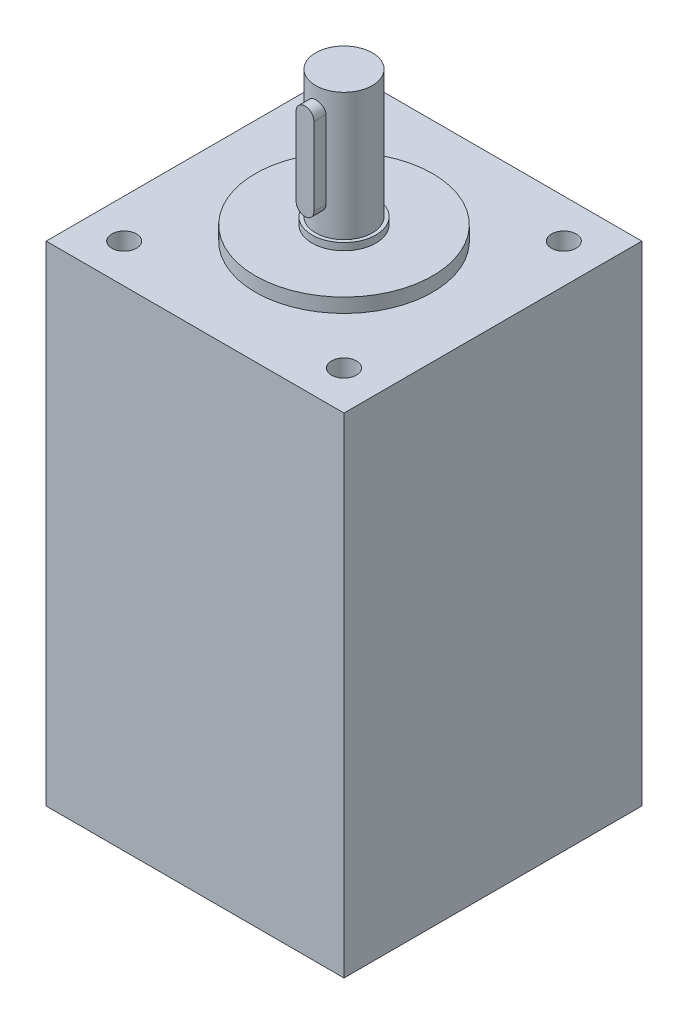
SolidWorks part; units mm, degrees
ref_plane "前视基准面" through (0, 0, 0) normal (0, 0, 1) x (1, 0, 0)
ref_plane "上视基准面" through (0, 0, 0) normal (0, 1, 0) x (1, 0, 0)
ref_plane "右视基准面" through (0, 0, 0) normal (1, 0, 0) x (0, 0, -1)
other "Configuration Table"
sketch "草图2" plane through (0, 0, 0) normal (0, 1, 0) x (1, 0, 0)
  line L1 (0, 0) -> (42, 0)
  line L2 (0, 0) -> (0, 42)
  line L3 (0, 42) -> (42, 42)
  line L4 (42, 0) -> (42, 42)
  dimension "D1" = 42
  dimension "D2" = 42
extrude "凸台-拉伸1" add sketch "草图2" along normal blind 69
sketch "草图3" plane through (0, 69, 0) normal (0, 1, 0) x (1, 0, 0)
  circle A0 centre (21, 21) radius 12.5
extrude "凸台-拉伸2" add sketch "草图3" along normal blind 2
sketch "草图4" plane through (0, 71, 0) normal (0, 1, 0) x (1, 0, 0)
  circle A0 centre (21, 21) radius 4.5
extrude "凸台-拉伸3" add sketch "草图4" along normal blind 1
sketch "草图5" plane through (0, 72, 0) normal (0, 1, 0) x (1, 0, 0)
  circle A0 centre (21, 21) radius 4
extrude "凸台-拉伸4" add sketch "草图5" along normal blind 18
ref_plane "基准面1" through (0, 0, -17) normal (0, 0, 1) x (1, 0, 0)
sketch "草图6" plane through (0, 0, -17) normal (0, 0, 1) x (1, 0, 0)
  line L0 (21, 79) -> (21, -49921) construction
  line L1 (25, 90) -> (17, 90) construction
  line L2 (21, 87) -> (21, 76) construction
  line L3 (22.2549, 87) -> (22.2549, 76)
  line L4 (19.7451, 87) -> (19.7451, 76)
  arc A0 (22.2549, 87) -> (19.7451, 87) centre (21, 87) ccw
  arc A1 (19.7451, 76) -> (22.2549, 76) centre (21, 76) ccw
  point P4 (21, 90)
  point P7 (21, 81.5)
  dimension "D1" = 3
  dimension "D2" = 11
extrude "凸台-拉伸5" add sketch "草图6" along normal blind 1.5 and the other way blind 4
sketch "草图7" plane through (0, 69, 0) normal (0, 1, 0) x (1, 0, 0)
  line L0 (42, 42) -> (0, 42) construction
  line L1 (0, 42) -> (0, 0) construction
  line L2 (21, 21) -> (21, 50021) construction
  line L3 (21, 21) -> (50021, 21) construction
  circle A0 centre (5.5, 36.5) radius 1.75
  circle A1 centre (36.5, 36.5) radius 1.75
  circle A2 centre (36.5, 5.5) radius 1.75
  circle A3 centre (5.5, 5.5) radius 1.75
  dimension "D1" = 3.5
  dimension "D2" = 5.5
  dimension "D3" = 5.5
extrude "切除-拉伸1" cut sketch "草图7" against normal blind 71.5
